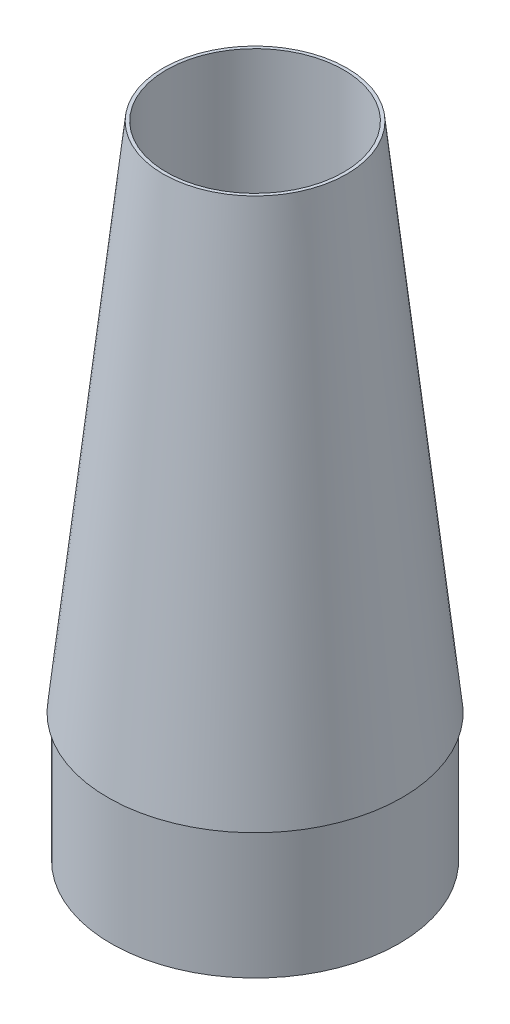
SolidWorks part; units mm, degrees
material "6061 Alloy"
ref_plane "Front Plane" through (0, 0, 0) normal (0, 0, 1) x (1, 0, 0)
ref_plane "Top Plane" through (0, 0, 0) normal (0, 1, 0) x (1, 0, 0)
ref_plane "Right Plane" through (0, 0, 0) normal (1, 0, 0) x (0, 0, -1)
sketch "Sketch1" plane through (0, 0, 0) normal (0, 0, 1) x (1, 0, 0)
  line L0 (0, 0) -> (0, 76.2)
  line L1 (0, 76.2) -> (32.8752, 381)
  line L2 (32.8752, 381) -> (87.5284, 381)
  line L3 (87.5284, 381) -> (87.5284, 0)
  line L4 (87.5284, 0) -> (0, 0)
  dimension "D1" = 87.5284
  dimension "D2" = 76.2
  dimension "D3" = 304.8
  dimension "D4" = 54.6532
revolve "Revolve1" add sketch "Sketch1" angle 360 about L3
sketch "Sketch2" plane through (0, 381, 0) normal (0, 1, 0) x (1, 0, 0)
  circle A0 centre (87.5284, 0) radius 52.7482
  dimension "D1" = 105.4964
extrude "Cut-Extrude1" cut sketch "Sketch2" against normal blind 203.2
sketch "Sketch3" plane through (0, 0, 0) normal (0, -1, 0) x (1, 0, 0)
  circle A0 centre (87.5284, 0) radius 85.6234
  dimension "D1" = 171.2468
extrude "Cut-Extrude2" cut sketch "Sketch3" against normal blind 76.2 flip side to cut
